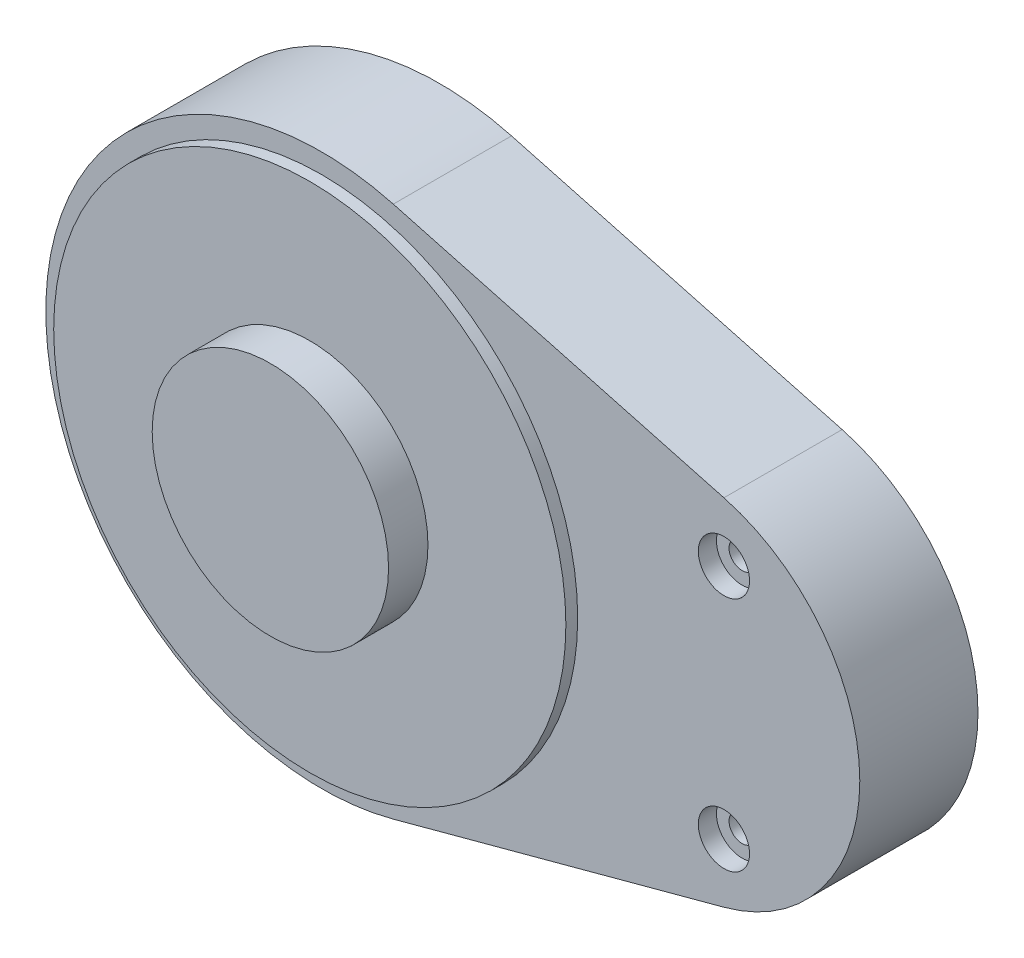
SolidWorks part; units mm, degrees
material "1060 Alloy"
ref_plane "Front Plane" through (0, 0, 0) normal (0, 0, 1) x (1, 0, 0)
ref_plane "Top Plane" through (0, 0, 0) normal (0, 1, 0) x (1, 0, 0)
ref_plane "Right Plane" through (0, 0, 0) normal (1, 0, 0) x (0, 0, -1)
sketch "Sketch1" plane through (0, 0, 0) normal (0, 0, 1) x (1, 0, 0)
  line L0 (12.1154, 172.0095) -> (-71.8019, 194.6026) construction
  line L1 (-71.8019, 59.4164) -> (12.1154, 82.0095) construction
  line L2 (12.1154, 172.0095) -> (-71.8019, 194.6026)
  line L3 (-71.8019, 59.4164) -> (12.1154, 82.0095)
  arc A0 (12.1154, 82.0095) -> (12.1154, 172.0095) centre (0, 127.0095) ccw construction
  arc A1 (-71.8019, 194.6026) -> (-71.8019, 59.4164) centre (-90, 127.0095) ccw construction
  arc A2 (12.1154, 82.0095) -> (12.1154, 172.0095) centre (0, 127.0095) ccw
  arc A3 (-71.8019, 194.6026) -> (-71.8019, 59.4164) centre (-90, 127.0095) ccw
extrude "Boss-Extrude1" add sketch "Sketch1" along normal blind 30
sketch "Sketch2" plane through (0, 0, 0) normal (0, 0, -1) x (-1, 0, 0)
  line L1 (105, 142.0095) -> (75, 142.0095)
  line L2 (105, 142.0095) -> (105, 112.0095)
  line L3 (105, 112.0095) -> (75, 112.0095)
  line L4 (75, 142.0095) -> (75, 112.0095)
extrude "Boss-Extrude2" add sketch "Sketch2" along normal blind 10
sketch "Sketch3" plane through (0, 0, 30) normal (0, 0, 1) x (1, 0, 0)
  circle A0 centre (-90, 127.0095) radius 65
  dimension "D1" = 130
extrude "Boss-Extrude3" add sketch "Sketch3" along normal blind 3
sketch "Sketch4" plane through (0, 0, 33) normal (0, 0, 1) x (1, 0, 0)
  circle A0 centre (-90, 127.0095) radius 30
  dimension "D1" = 60
extrude "Boss-Extrude4" add sketch "Sketch4" along normal blind 10
hole_wizard "CBORE for M6 Pan Head Screw1" positions "3DSketch1" profile "Sketch5" counterbore size "M6" standard "ISO"
sketch3d "3DSketch1"
  line L0 (46.6024, 127.0095, 30) -> (-16.395, 127.0095, 30) construction
  arc A0 (12.1154, 82.0095, 30) -> (12.1154, 172.0095, 30) centre (0, 127.0095, 30) ccw construction
  point P0 (12.1154, 157.0095, 30)
  point P2 (12.1154, 97.0095, 30)
  point P14 (0, 127.0095, 76.6024)
  dimension "D1" = 60
  dimension "D2" = 60
sketch "Sketch5" plane through (12.1154, 157.0095, 30) normal (1, 0, 0) x (0, -1, 0)
  line L0 (0, 0) -> (0, 52.4828)
  line L1 (0, 52.4828) -> (3.3, 50.5)
  line L2 (3.3, 50.5) -> (3.3, 4.6)
  line L3 (3.3, 4.6) -> (6.5, 4.6)
  line L4 (6.5, 4.6) -> (6.5, 0)
  line L5 (6.5, 0) -> (0, 0)
  line L10 (0, 52.4828) -> (-3.3, 50.5) construction
  line L11 (0, -6.35) -> (0, 107.95) construction
  dimension "Hole Dia." = 6.6
  dimension "Hole Depth" = 50.5
  dimension "C'Bore Dia." = 13
  dimension "C'Bore Depth" = 4.6
  dimension "Drill Angle" = 118
